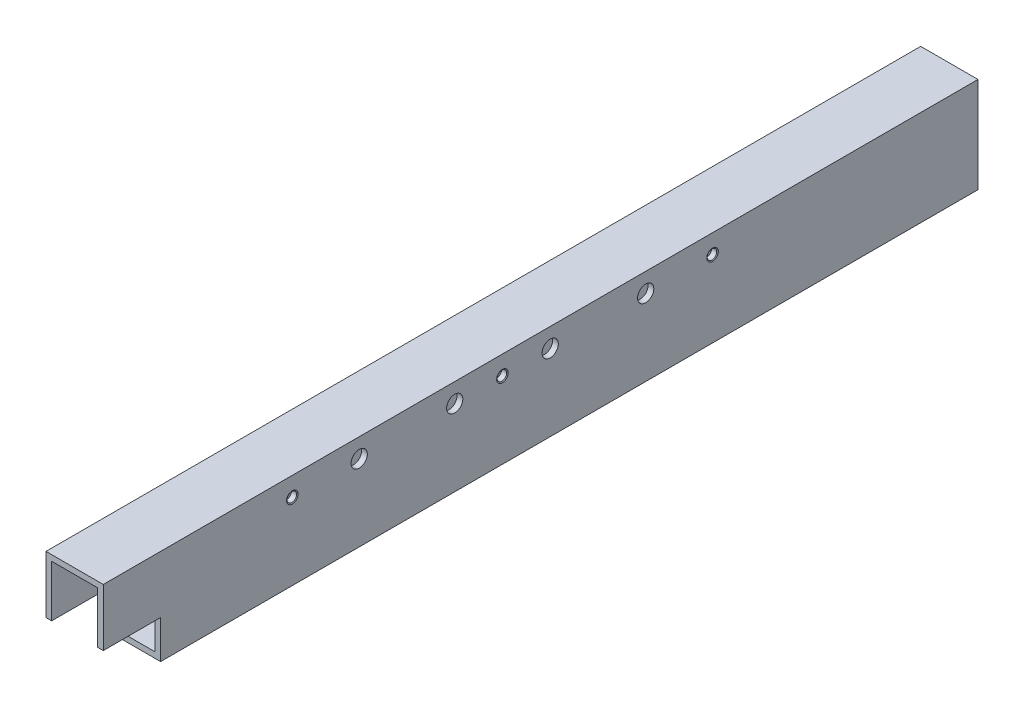
SolidWorks part; units mm, degrees
material "Д16Т ГОСТ 4784-74"
ref_plane "Спереди" through (0, 0, 0) normal (0, 0, 1) x (1, 0, 0)
ref_plane "Сверху" through (0, 0, 0) normal (0, 1, 0) x (1, 0, 0)
ref_plane "Справа" through (0, 0, 0) normal (1, 0, 0) x (0, 0, -1)
sketch "Эскиз1" plane through (0, 0, 0) normal (0, 0, 1) x (1, 0, 0)
  line L1 (0, 0) -> (30, 0)
  line L2 (0, 0) -> (0, 50)
  line L3 (0, 50) -> (30, 50)
  line L4 (30, 0) -> (30, 50)
  dimension "D1" = 50
  dimension "D2" = 30
extrude "Вытянуть-Тонкостенный1" add sketch "Эскиз1" along normal blind 458 thin thin type one direction reverse wall 3
sketch "Эскиз2" plane through (30, 0, 0) normal (1, 0, 0) x (0, 0, -1)
  line L1 (-458, 0) -> (-428, 0)
  line L2 (-458, 0) -> (-458, 20)
  line L3 (-458, 20) -> (-428, 20)
  line L4 (-428, 0) -> (-428, 20)
  dimension "D1" = 20
  dimension "D2" = 30
extrude "Вырез-Вытянуть1" cut sketch "Эскиз2" against normal through all
hole_wizard "Отверстие обработанное метчиком M61" positions "Эскиз4" profile "Эскиз3" tap size "M6" standard "DIN"
sketch "Эскиз4" plane through (30, 0, 0) normal (1, 0, 0) x (0, 0, -1)
  line L0 (-458, 50) -> (0, 50) construction
  line L1 (-249, 40) -> (-249, 50) construction
  line L3 (-458, 20) -> (-458, 50) construction
  point P0 (-249, 40)
  point P7 (-359, 40)
  point P13 (-139, 40)
  dimension "D1" = 10
  dimension "D2" = 110
  dimension "D3" = 209
sketch "Эскиз3" plane through (30, 40, 249) normal (0, 1, 0) x (0, 0, -1)
  line L0 (0, 0) -> (0, 18.5022)
  line L1 (0, 18.5022) -> (2.5, 17)
  line L2 (2.5, 17) -> (2.5, 0.3031)
  line L3 (2.5, 0.3031) -> (3.025, 0)
  line L5 (3.025, 0) -> (0, 0)
  line L6 (-2.5, 0.3031) -> (-3.025, 0) construction
  line L10 (0, 18.5022) -> (-2.5, 17) construction
  line L11 (0, -6.35) -> (0, 107.95) construction
  dimension "Диаметр сверла" = 5
  dimension "Глубина сверла" = 17
  dimension "Диаметр передней зенковки" = 6.05
  dimension "Угол передней зенковки" = 120
  dimension "Угол заточки сверла" = 118
cosmetic thread "Отверстие резьбы1" parameters "D1"=3, "D2"=6
cosmetic thread "Отверстие резьбы2" parameters "D1"=3, "D2"=6
cosmetic thread "Отверстие резьбы3" parameters "D1"=3, "D2"=6
hole_wizard "Отверстие обработанное метчиком M101" positions "Эскиз6" profile "Эскиз5" tap size "M10" standard "DIN"
sketch "Эскиз6" plane through (0, 0, 0) normal (-1, 0, 0) x (0, 0, 1)
  line L0 (249, 50) -> (249, 7.9738) construction
  line L1 (458, 50) -> (0, 50) construction
  line L3 (458, 20) -> (458, 50) construction
  point P0 (224, 40)
  point P1 (174, 40)
  point P10 (324, 40)
  point P11 (274, 40)
  dimension "D1" = 10
  dimension "D2" = 50
  dimension "D3" = 50
  dimension "D4" = 209
sketch "Эскиз5" plane through (0, 40, 224) normal (0, 1, 0) x (0, 0, 1)
  line L0 (0, 0) -> (0, 50.0537)
  line L1 (0, 50.0537) -> (4.25, 47.5)
  line L2 (4.25, 47.5) -> (4.25, 0.4474)
  line L3 (4.25, 0.4474) -> (5.025, 0)
  line L5 (5.025, 0) -> (0, 0)
  line L6 (-4.25, 0.4474) -> (-5.025, 0) construction
  line L10 (0, 50.0537) -> (-4.25, 47.5) construction
  line L11 (0, -6.35) -> (0, 107.95) construction
  dimension "Диаметр сверла" = 8.5
  dimension "Глубина сверла" = 47.5
  dimension "Диаметр передней зенковки" = 10.05
  dimension "Угол передней зенковки" = 120
  dimension "Угол заточки сверла" = 118
cosmetic thread "Отверстие резьбы4" parameters "D1"=30, "D2"=10
cosmetic thread "Отверстие резьбы5" parameters "D1"=30, "D2"=10
cosmetic thread "Отверстие резьбы6" parameters "D1"=30, "D2"=10
cosmetic thread "Отверстие резьбы7" parameters "D1"=30, "D2"=10
